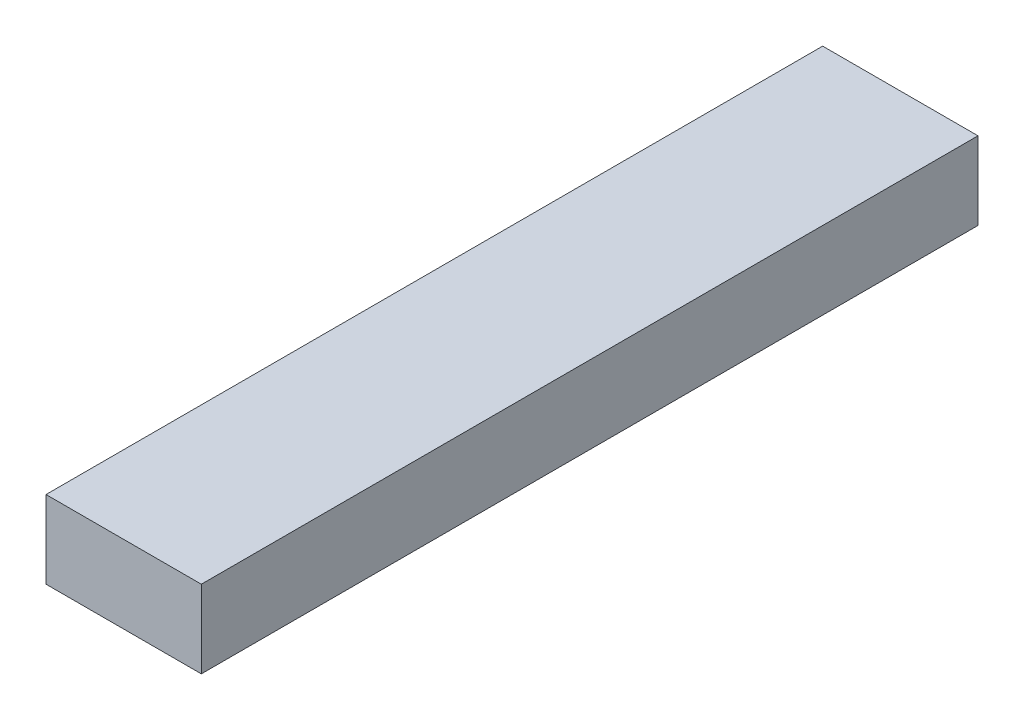
SolidWorks part; units mm, degrees
ref_plane "Front Plane" through (0, 0, 0) normal (0, 0, 1) x (1, 0, 0)
ref_plane "Top Plane" through (0, 0, 0) normal (0, 1, 0) x (1, 0, 0)
ref_plane "Right Plane" through (0, 0, 0) normal (1, 0, 0) x (0, 0, -1)
sketch "Sketch1" plane through (0, 0, 0) normal (0, 0, 1) x (1, 0, 0)
  line L1 (0, 0) -> (10, 0)
  line L2 (0, 0) -> (0, 5)
  line L3 (0, 5) -> (10, 5)
  line L4 (10, 0) -> (10, 5)
  dimension "D1" = 10
  dimension "D2" = 5
extrude "Boss-Extrude1" add sketch "Sketch1" along normal blind 50
